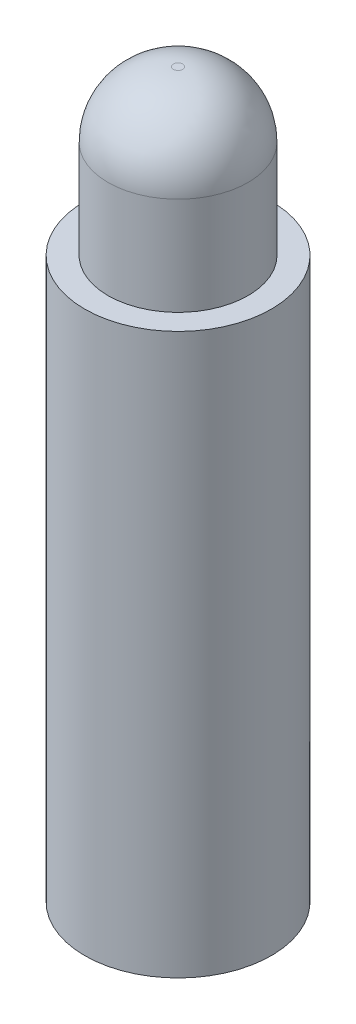
SolidWorks part; units mm, degrees
ref_plane "Front Plane" through (0, 0, 0) normal (0, 0, 1) x (1, 0, 0)
ref_plane "Top Plane" through (0, 0, 0) normal (0, 1, 0) x (1, 0, 0)
ref_plane "Right Plane" through (0, 0, 0) normal (1, 0, 0) x (0, 0, -1)
sketch "Sketch1" plane through (0, 0, 0) normal (0, 1, 0) x (1, 0, 0)
  circle A0 centre (0, 0) radius 2
  dimension "D1" = 4
extrude "Boss-Extrude1" add sketch "Sketch1" along normal blind 12
sketch "Sketch2" plane through (0, 12, 0) normal (0, 1, 0) x (1, 0, 0)
  circle A0 centre (0, 0) radius 1.5
  dimension "D1" = 3
extrude "Boss-Extrude2" add sketch "Sketch2" along normal blind 3.5
fillet "Fillet1" radius 1.4 1 edges at (0, 15.5, 1.5)
